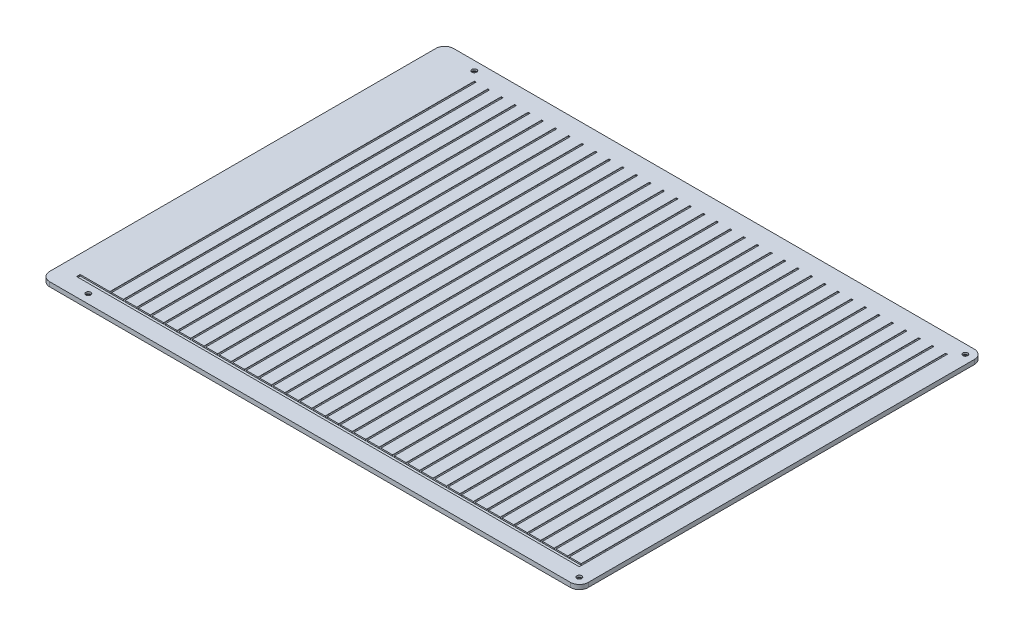
SolidWorks part; units mm, degrees
material "Alumina"
ref_plane "Front Plane" through (0, 0, 0) normal (0, 0, 1) x (1, 0, 0)
ref_plane "Top Plane" through (0, 0, 0) normal (0, 1, 0) x (1, 0, 0)
ref_plane "Right Plane" through (0, 0, 0) normal (1, 0, 0) x (0, 0, -1)
sketch "Sketch1" plane through (0, 0, 0) normal (0, 1, 0) x (1, 0, 0)
  line L1 (-300, -225) -> (300, -225)
  line L2 (-300, -225) -> (-300, 225)
  line L3 (-300, 225) -> (300, 225)
  line L4 (300, -225) -> (300, 225)
  line L5 (-300, -225) -> (300, 225) construction
  line L6 (-300, 225) -> (300, -225) construction
  point P0 (0, 0)
  dimension "D1" = 450
  dimension "D2" = 600
extrude "Boss-Extrude1" add sketch "Sketch1" along normal blind 5
sketch "Sketch2" plane through (0, 0, 225) normal (0, 0, 1) x (1, 0, 0)
  line L0 (280, 5) -> (280, 0) construction
  line L1 (-300, 5) -> (300, 5) construction
  line L2 (-300, 0) -> (300, 0) construction
  line L3 (300, 5) -> (300, 0) construction
  line L4 (280, 4.5) -> (280, 5)
  line L5 (280, 5) -> (278, 5)
  line L6 (278, 5) -> (278, 4.5)
  line L7 (263, 5) -> (263, 4.5)
  line L8 (265, 4.5) -> (265, 5)
  line L9 (265, 5) -> (263, 5)
  line L10 (248, 5) -> (248, 4.5)
  line L11 (250, 4.5) -> (250, 5)
  line L12 (250, 5) -> (248, 5)
  line L13 (233, 5) -> (233, 4.5)
  line L14 (235, 4.5) -> (235, 5)
  line L15 (235, 5) -> (233, 5)
  line L16 (218, 5) -> (218, 4.5)
  line L17 (220, 4.5) -> (220, 5)
  line L18 (220, 5) -> (218, 5)
  line L19 (203, 5) -> (203, 4.5)
  line L20 (205, 4.5) -> (205, 5)
  line L21 (205, 5) -> (203, 5)
  line L22 (188, 5) -> (188, 4.5)
  line L23 (190, 4.5) -> (190, 5)
  line L24 (190, 5) -> (188, 5)
  line L25 (173, 5) -> (173, 4.5)
  line L26 (175, 4.5) -> (175, 5)
  line L27 (175, 5) -> (173, 5)
  line L28 (158, 5) -> (158, 4.5)
  line L29 (160, 4.5) -> (160, 5)
  line L30 (160, 5) -> (158, 5)
  line L31 (143, 5) -> (143, 4.5)
  line L32 (145, 4.5) -> (145, 5)
  line L33 (145, 5) -> (143, 5)
  line L34 (128, 5) -> (128, 4.5)
  line L35 (130, 4.5) -> (130, 5)
  line L36 (130, 5) -> (128, 5)
  line L37 (113, 5) -> (113, 4.5)
  line L38 (115, 4.5) -> (115, 5)
  line L39 (115, 5) -> (113, 5)
  line L40 (98, 5) -> (98, 4.5)
  line L41 (100, 4.5) -> (100, 5)
  line L42 (100, 5) -> (98, 5)
  line L43 (83, 5) -> (83, 4.5)
  line L44 (85, 4.5) -> (85, 5)
  line L45 (85, 5) -> (83, 5)
  line L46 (68, 5) -> (68, 4.5)
  line L47 (70, 4.5) -> (70, 5)
  line L48 (70, 5) -> (68, 5)
  line L49 (53, 5) -> (53, 4.5)
  line L50 (55, 4.5) -> (55, 5)
  line L51 (55, 5) -> (53, 5)
  line L52 (38, 5) -> (38, 4.5)
  line L53 (40, 4.5) -> (40, 5)
  line L54 (40, 5) -> (38, 5)
  line L55 (23, 5) -> (23, 4.5)
  line L56 (25, 4.5) -> (25, 5)
  line L57 (25, 5) -> (23, 5)
  line L58 (8, 5) -> (8, 4.5)
  line L59 (10, 4.5) -> (10, 5)
  line L60 (10, 5) -> (8, 5)
  line L61 (-7, 5) -> (-7, 4.5)
  line L62 (-5, 4.5) -> (-5, 5)
  line L63 (-5, 5) -> (-7, 5)
  line L64 (-22, 5) -> (-22, 4.5)
  line L65 (-20, 4.5) -> (-20, 5)
  line L66 (-20, 5) -> (-22, 5)
  line L67 (-37, 5) -> (-37, 4.5)
  line L68 (-35, 4.5) -> (-35, 5)
  line L69 (-35, 5) -> (-37, 5)
  line L70 (-52, 5) -> (-52, 4.5)
  line L71 (-50, 4.5) -> (-50, 5)
  line L72 (-50, 5) -> (-52, 5)
  line L73 (-67, 5) -> (-67, 4.5)
  line L74 (-65, 4.5) -> (-65, 5)
  line L75 (-65, 5) -> (-67, 5)
  line L76 (-82, 5) -> (-82, 4.5)
  line L77 (-80, 4.5) -> (-80, 5)
  line L78 (-80, 5) -> (-82, 5)
  line L79 (-97, 5) -> (-97, 4.5)
  line L80 (-95, 4.5) -> (-95, 5)
  line L81 (-95, 5) -> (-97, 5)
  line L82 (-112, 5) -> (-112, 4.5)
  line L83 (-110, 4.5) -> (-110, 5)
  line L84 (-110, 5) -> (-112, 5)
  line L85 (-127, 5) -> (-127, 4.5)
  line L86 (-125, 4.5) -> (-125, 5)
  line L87 (-125, 5) -> (-127, 5)
  line L88 (-142, 5) -> (-142, 4.5)
  line L89 (-140, 4.5) -> (-140, 5)
  line L90 (-140, 5) -> (-142, 5)
  line L91 (-157, 5) -> (-157, 4.5)
  line L92 (-155, 4.5) -> (-155, 5)
  line L93 (-155, 5) -> (-157, 5)
  line L94 (-172, 5) -> (-172, 4.5)
  line L95 (-170, 4.5) -> (-170, 5)
  line L96 (-170, 5) -> (-172, 5)
  line L97 (-187, 5) -> (-187, 4.5)
  line L98 (-185, 4.5) -> (-185, 5)
  line L99 (-185, 5) -> (-187, 5)
  line L100 (-202, 5) -> (-202, 4.5)
  line L101 (-200, 4.5) -> (-200, 5)
  line L102 (-200, 5) -> (-202, 5)
  line L103 (-217, 5) -> (-217, 4.5)
  line L104 (-215, 4.5) -> (-215, 5)
  line L105 (-215, 5) -> (-217, 5)
  line L106 (-232, 5) -> (-232, 4.5)
  line L107 (-230, 4.5) -> (-230, 5)
  line L108 (-230, 5) -> (-232, 5)
  line L109 (-247, 5) -> (-247, 4.5)
  line L110 (-245, 4.5) -> (-245, 5)
  line L111 (-245, 5) -> (-247, 5)
  line L112 (278, 5) -> (263, 5) construction
  arc A0 (278, 4.5) -> (280, 4.5) centre (279, 4.5) ccw
  arc A1 (263, 4.5) -> (265, 4.5) centre (264, 4.5) ccw
  arc A2 (248, 4.5) -> (250, 4.5) centre (249, 4.5) ccw
  arc A3 (233, 4.5) -> (235, 4.5) centre (234, 4.5) ccw
  arc A4 (218, 4.5) -> (220, 4.5) centre (219, 4.5) ccw
  arc A5 (203, 4.5) -> (205, 4.5) centre (204, 4.5) ccw
  arc A6 (188, 4.5) -> (190, 4.5) centre (189, 4.5) ccw
  arc A7 (173, 4.5) -> (175, 4.5) centre (174, 4.5) ccw
  arc A8 (158, 4.5) -> (160, 4.5) centre (159, 4.5) ccw
  arc A9 (143, 4.5) -> (145, 4.5) centre (144, 4.5) ccw
  arc A10 (128, 4.5) -> (130, 4.5) centre (129, 4.5) ccw
  arc A11 (113, 4.5) -> (115, 4.5) centre (114, 4.5) ccw
  arc A12 (98, 4.5) -> (100, 4.5) centre (99, 4.5) ccw
  arc A13 (83, 4.5) -> (85, 4.5) centre (84, 4.5) ccw
  arc A14 (68, 4.5) -> (70, 4.5) centre (69, 4.5) ccw
  arc A15 (53, 4.5) -> (55, 4.5) centre (54, 4.5) ccw
  arc A16 (38, 4.5) -> (40, 4.5) centre (39, 4.5) ccw
  arc A17 (23, 4.5) -> (25, 4.5) centre (24, 4.5) ccw
  arc A18 (8, 4.5) -> (10, 4.5) centre (9, 4.5) ccw
  arc A19 (-7, 4.5) -> (-5, 4.5) centre (-6, 4.5) ccw
  arc A20 (-22, 4.5) -> (-20, 4.5) centre (-21, 4.5) ccw
  arc A21 (-37, 4.5) -> (-35, 4.5) centre (-36, 4.5) ccw
  arc A22 (-52, 4.5) -> (-50, 4.5) centre (-51, 4.5) ccw
  arc A23 (-67, 4.5) -> (-65, 4.5) centre (-66, 4.5) ccw
  arc A24 (-82, 4.5) -> (-80, 4.5) centre (-81, 4.5) ccw
  arc A25 (-97, 4.5) -> (-95, 4.5) centre (-96, 4.5) ccw
  arc A26 (-112, 4.5) -> (-110, 4.5) centre (-111, 4.5) ccw
  arc A27 (-127, 4.5) -> (-125, 4.5) centre (-126, 4.5) ccw
  arc A28 (-142, 4.5) -> (-140, 4.5) centre (-141, 4.5) ccw
  arc A29 (-157, 4.5) -> (-155, 4.5) centre (-156, 4.5) ccw
  arc A30 (-172, 4.5) -> (-170, 4.5) centre (-171, 4.5) ccw
  arc A31 (-187, 4.5) -> (-185, 4.5) centre (-186, 4.5) ccw
  arc A32 (-202, 4.5) -> (-200, 4.5) centre (-201, 4.5) ccw
  arc A33 (-217, 4.5) -> (-215, 4.5) centre (-216, 4.5) ccw
  arc A34 (-232, 4.5) -> (-230, 4.5) centre (-231, 4.5) ccw
  arc A35 (-247, 4.5) -> (-245, 4.5) centre (-246, 4.5) ccw
  dimension "D3" = 1
  dimension "D1" = 20
  dimension "D2" = 0.5
  dimension "D5" = 15
  dimension "D4" = 36
extrude "Cut-Extrude1" cut sketch "Sketch2" against normal offset from surface (410 mm away) 20 from offset 20 up to face at (0, 2.5, -225) offset against normal yes
sketch "Sketch3" plane through (280, 0, 0) normal (-1, 0, 0) x (0, 0, 1)
  line L1 (205, 5) -> (201, 5)
  line L2 (205, 5) -> (205, 3.5)
  line L3 (205, 3.5) -> (201, 3.5)
  line L4 (201, 5) -> (201, 3.5)
  line L5 (205, 4.5) -> (205, 3.5) construction
  line L6 (205, 4.5) -> (205, 3.5) construction
  dimension "D1" = 4
extrude "Cut-Extrude2" cut sketch "Sketch3" along normal offset from surface (560 mm away) 20 up to face at (-300, 2.5, 0)
sketch "Sketch4" plane through (0, 0, 0) normal (0, 1, 0) x (1, 0, 0)
  line L0 (-247, 205) -> (-247, -201) construction
  line L1 (280, -205) -> (300, -225) construction
  line L2 (280, 205) -> (300, 225) construction
  line L3 (-247, 205) -> (-247, -201) construction
  line L5 (-247, 205) -> (-267, 225) construction
  line L6 (300, 225) -> (-300, 225) construction
  line L7 (-247, -205) -> (-267, -225) construction
  line L10 (280, -205) -> (-280, -205) construction
  line L11 (-300, -225) -> (300, -225) construction
  point P12 (-257, 215)
  point P19 (290, -215)
  point P20 (290, 215)
  point P31 (-257, -215)
  dimension "D1" = 45
  dimension "D2" = 45
fillet "Fillet2" radius 10 4 edges at (-300, 2.5, -225) (-300, 2.5, 225) (300, 2.5, 225) (300, 2.5, -225)
hole_wizard "CSK for M5 SFHCS4" positions "3DSketch5" profile "Sketch10" countersink size "M5" standard "ANSI Metric" end condition through all
sketch3d "3DSketch5"
  point P0 (-257, 0, 215)
  point P3 (-257, 0, -215)
  point P6 (290, 0, -215)
  point P9 (290, 0, 215)
sketch "Sketch10" plane through (-257, 0, 215) normal (1, 0, 0) x (0, 0, -1)
  line L0 (0, 0) -> (0, 5)
  line L1 (0, 5) -> (2.75, 5)
  line L2 (2.75, 5) -> (2.75, 2.85)
  line L3 (2.75, 2.85) -> (5.6, 0)
  line L5 (5.6, 0) -> (0, 0)
  line L6 (-2.75, 2.85) -> (-5.6, 0) construction
  line L11 (0, -6.35) -> (0, 107.95) construction
  dimension "Thru Hole Dia." = 5.5
  dimension "Thru Hole Depth" = 5
  dimension "Near C'Sink Dia." = 11.2
  dimension "Near C'Sink Angle" = 90
equation "\"plate_width\"= 45cm"
equation "\"D1@Sketch1\"=\"plate_width\""
equation "\"plate_length\"= 60cm"
equation "\"D2@Sketch1\"=\"plate_length\""
equation "\"half_plate_thickness\"= 0.5cm"
equation "\"D1@Boss-Extrude1\"=\"half_plate_thickness\""
equation "\"general_tolerance\"= 0.5mm"
equation "\"eds_count\"= 36"
equation "\"eds_radius\"= 0.1cm"
equation "\"wall_width\"= 2cm"
equation "\"D1@Sketch2\"=\"wall_width\""
equation "\"D2@Sketch2\"=\"general_tolerance\""
equation "\"D3@Sketch2\"=\"eds_radius\""
equation "\"eds_spacing\"= 1.5cm"
equation "\"D5@Sketch2\"=\"eds_spacing\""
equation "\"D4@Sketch2\"=\"eds_count\""
equation "\"D19@Cut-Extrude1\"=\"wall_width\""
equation "\"D1@Cut-Extrude1\"=\"wall_width\""
equation "\"D1@Sketch3\"=\"eds_radius\"*4"
equation "\"D1@Cut-Extrude2\"=\"wall_width\""
equation "\"plate_fillet_radius\"= 1cm"
equation "\"D1@Fillet2\"=\"plate_fillet_radius\""
